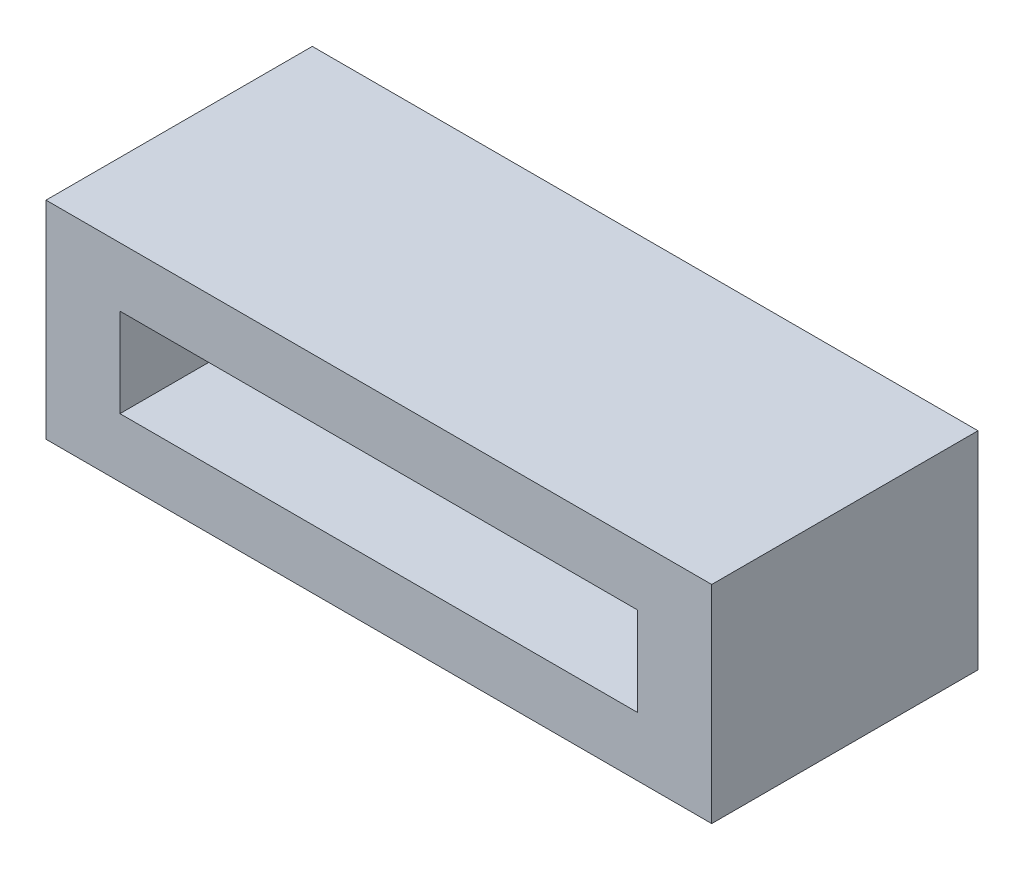
SolidWorks part; units mm, degrees
ref_plane "Front Plane" through (0, 0, 0) normal (0, 0, 1) x (1, 0, 0)
ref_plane "Top Plane" through (0, 0, 0) normal (0, 1, 0) x (1, 0, 0)
ref_plane "Right Plane" through (0, 0, 0) normal (1, 0, 0) x (0, 0, -1)
sketch "Sketch1" plane through (0, 0, 0) normal (0, 0, 1) x (1, 0, 0)
  line L1 (-17.5, 3) -> (17.5, 3)
  line L2 (-17.5, 3) -> (-17.5, -3)
  line L3 (-17.5, -3) -> (17.5, -3)
  line L4 (17.5, 3) -> (17.5, -3)
  line L5 (-17.5, 3) -> (17.5, -3) construction
  line L6 (-17.5, -3) -> (17.5, 3) construction
  line L7 (-22.5, 7) -> (22.5, 7)
  line L8 (-22.5, 7) -> (-22.5, -7)
  line L9 (-22.5, -7) -> (22.5, -7)
  line L10 (22.5, 7) -> (22.5, -7)
  line L11 (-22.5, 7) -> (22.5, -7) construction
  line L12 (-22.5, -7) -> (22.5, 7) construction
  point P0 (0, 0)
  point P6 (0, 0)
extrude "Boss-Extrude1" add sketch "Sketch1" along normal blind 18
